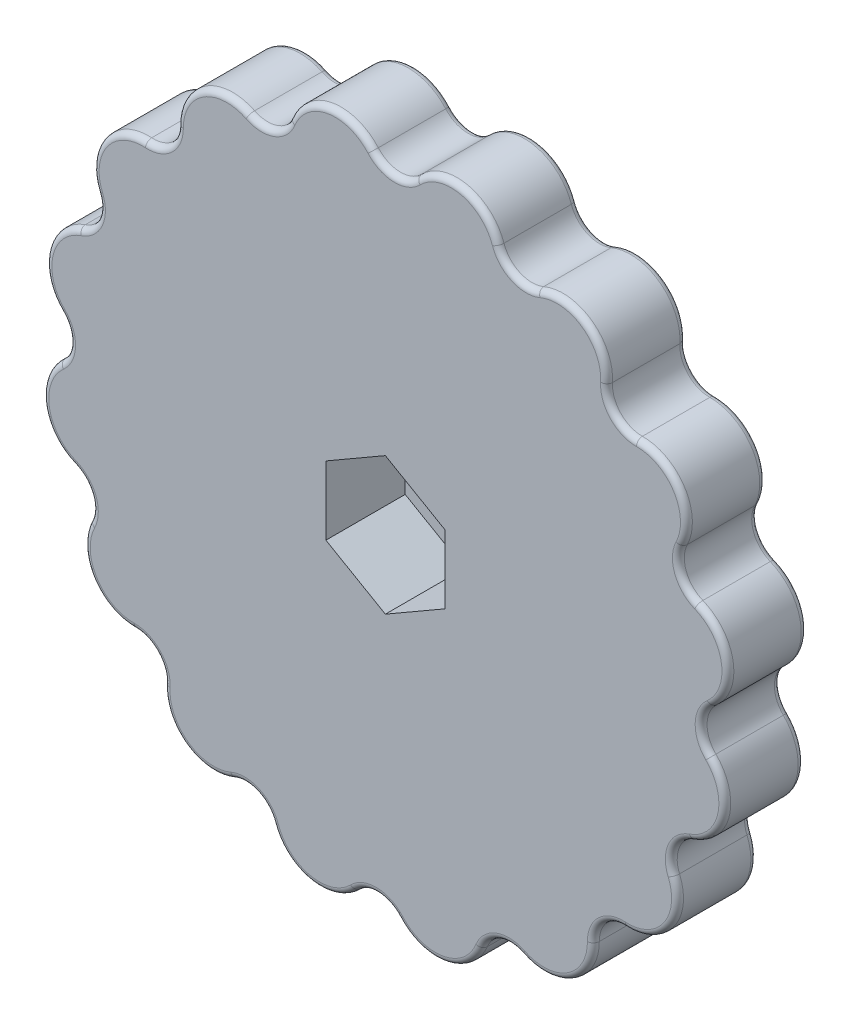
SolidWorks part; units mm, degrees
material "ABS"
ref_plane "Front Plane" through (0, 0, 0) normal (0, 0, 1) x (1, 0, 0)
ref_plane "Top Plane" through (0, 0, 0) normal (0, 1, 0) x (1, 0, 0)
ref_plane "Right Plane" through (0, 0, 0) normal (1, 0, 0) x (0, 0, -1)
ref_plane "Plane1" through (0, 0, 2) normal (0, 0, -1) x (-1, 0, 0)
sketch "Sketch1" plane through (0, 0, 2) normal (0, 0, -1) x (-1, 0, 0)
  line L193 (-20.6157, 1.931) -> (20.5827, 1.931) construction
  arc A1 (-1.5391, 16.3806) -> (0.6549, 16.4397) centre (-0.4696, 17.4324) ccw
  arc A32 (4.8467, 15.7227) -> (6.8963, 14.9377) centre (6.2372, 16.2852) ccw
  arc A33 (0.6549, 16.4397) -> (4.8467, 15.7227) centre (2.5291, 14.7853) cw
  arc A34 (6.8963, 14.9377) -> (10.4946, 12.6712) centre (7.9947, 12.6919) cw
  arc A38 (10.4946, 12.6712) -> (12.0877, 11.1616) centre (11.9945, 12.6587) ccw
  arc A39 (12.0877, 11.1616) -> (14.5448, 7.6905) centre (12.2431, 8.6664) cw
  arc A40 (14.5448, 7.6905) -> (15.439, 5.6862) centre (15.9258, 7.105) ccw
  arc A44 (15.439, 5.6862) -> (16.3806, 1.5391) centre (14.6276, 3.3215) cw
  arc A45 (16.3806, 1.5391) -> (16.4397, -0.6549) centre (17.4324, 0.4696) ccw
  arc A46 (16.4397, -0.6549) -> (15.7227, -4.8467) centre (14.7853, -2.5291) cw
  arc A50 (15.7227, -4.8467) -> (14.9377, -6.8963) centre (16.2852, -6.2372) ccw
  arc A51 (14.9377, -6.8963) -> (12.6712, -10.4946) centre (12.6919, -7.9947) cw
  arc A52 (12.6712, -10.4946) -> (11.1616, -12.0877) centre (12.6587, -11.9945) ccw
  arc A56 (11.1616, -12.0877) -> (7.6905, -14.5448) centre (8.6664, -12.2431) cw
  arc A57 (7.6905, -14.5448) -> (5.6862, -15.439) centre (7.105, -15.9258) ccw
  arc A58 (5.6862, -15.439) -> (1.5391, -16.3806) centre (3.3215, -14.6276) cw
  arc A62 (1.5391, -16.3806) -> (-0.6549, -16.4397) centre (0.4696, -17.4324) ccw
  arc A63 (-0.6549, -16.4397) -> (-4.8467, -15.7227) centre (-2.5291, -14.7853) cw
  arc A64 (-4.8467, -15.7227) -> (-6.8963, -14.9377) centre (-6.2372, -16.2852) ccw
  arc A68 (-6.8963, -14.9377) -> (-10.4946, -12.6712) centre (-7.9947, -12.6919) cw
  arc A69 (-10.4946, -12.6712) -> (-12.0877, -11.1616) centre (-11.9945, -12.6587) ccw
  arc A70 (-12.0877, -11.1616) -> (-14.5448, -7.6905) centre (-12.2431, -8.6664) cw
  arc A74 (-14.5448, -7.6905) -> (-15.439, -5.6862) centre (-15.9258, -7.105) ccw
  arc A75 (-15.439, -5.6862) -> (-16.3806, -1.5391) centre (-14.6276, -3.3215) cw
  arc A76 (-16.3806, -1.5391) -> (-16.4397, 0.6549) centre (-17.4324, -0.4696) ccw
  arc A77 (-16.4397, 0.6549) -> (-15.7227, 4.8467) centre (-14.7853, 2.5291) cw
  arc A80 (-15.7227, 4.8467) -> (-14.9377, 6.8963) centre (-16.2852, 6.2372) ccw
  arc A83 (-14.9377, 6.8963) -> (-12.6712, 10.4946) centre (-12.6919, 7.9947) cw
  arc A86 (-12.6712, 10.4946) -> (-11.1616, 12.0877) centre (-12.6587, 11.9945) ccw
  arc A89 (-11.1616, 12.0877) -> (-7.6905, 14.5448) centre (-8.6664, 12.2431) cw
  arc A92 (-7.6905, 14.5448) -> (-5.6862, 15.439) centre (-7.105, 15.9258) ccw
  arc A95 (-5.6862, 15.439) -> (-1.5391, 16.3806) centre (-3.3215, 14.6276) cw
  point P79 (0, 0)
  point P108 (0, 0)
  point P252 (0, 0)
  dimension "D1" = 2.5
  dimension "D2" = 3
  dimension "D3" = 16
  dimension "D5" = 30
extrude "Boss-Extrude1" add sketch "Sketch1" against normal blind 4
sketch "Sketch2" plane through (0, 0, 2) normal (0, 0, -1) x (-1, 0, 0)
  circle A0 centre (0, 0) radius 6
  dimension "D1" = 12
extrude "Boss-Extrude2" add sketch "Sketch2" along normal blind 2
sketch "Sketch3" plane through (0, 0, 6) normal (0, 0, -1) x (-1, 0, 0)
  circle A0 centre (0, 0) radius 1.8
  dimension "D1" = 3.6
extrude "Cut-Extrude1" cut sketch "Sketch3" along normal up to next
sketch "Sketch4" plane through (0, 0, 6) normal (0, 0, 1) x (1, 0, 0)
  line L7 (0, 3.4641) -> (-3, 1.7321)
  line L8 (-3, 1.7321) -> (-3, -1.7321)
  line L9 (-3, -1.7321) -> (0, -3.4641)
  line L10 (0, -3.4641) -> (3, -1.7321)
  line L11 (3, -1.7321) -> (3, 1.7321)
  line L12 (3, 1.7321) -> (0, 3.4641)
  circle A0 centre (0, 0) radius 3 construction
  dimension "D1" = 6
extrude "Cut-Extrude2" cut sketch "Sketch4" against normal blind 4
fillet "Fillet1" radius 0.5 1 edges at (6, 0, 2)
fillet "Fillet2" radius 0.3 64 edges at (0.4292, 15.933, 6) (0.4292, 15.933, 2) (-2.9506, 17.2495, 6) (-5.7007, 14.8844, 6) (-9.3271, 14.8073, 6) (-10.9628, 11.5698, 6) (-14.2836, 10.1108, 6) (-14.5559, 6.4939, 6) (-17.0656, 3.8751, 6) (-15.933, 0.4292, 6) (-17.2495, -2.9506, 6) (-14.8844, -5.7007, 6) (-14.8073, -9.3271, 6) (-11.5698, -10.9628, 6) (-10.1108, -14.2836, 6) (-6.4939, -14.5559, 6) (-3.8751, -17.0656, 6) (-0.4292, -15.933, 6) (2.9506, -17.2495, 6) (5.7007, -14.8844, 6) (9.3271, -14.8073, 6) (10.9628, -11.5698, 6) (14.2836, -10.1108, 6) (14.5559, -6.4939, 6) (17.0656, -3.8751, 6) (15.933, -0.4292, 6) (17.2495, 2.9506, 6) (14.8844, 5.7007, 6) (14.8073, 9.3271, 6) (11.5698, 10.9628, 6) (10.1108, 14.2836, 6) (6.4939, 14.5559, 6) (3.8751, 17.0656, 6) (-2.9506, 17.2495, 2) (-5.7007, 14.8844, 2) (-9.3271, 14.8073, 2) (-10.9628, 11.5698, 2) (-14.2836, 10.1108, 2) (-14.5559, 6.4939, 2) (-17.0656, 3.8751, 2) (-15.933, 0.4292, 2) (-17.2495, -2.9506, 2) (-14.8844, -5.7007, 2) (-14.8073, -9.3271, 2) (-11.5698, -10.9628, 2) (-10.1108, -14.2836, 2) (-6.4939, -14.5559, 2) (-3.8751, -17.0656, 2) (-0.4292, -15.933, 2) (2.9506, -17.2495, 2) (5.7007, -14.8844, 2) (9.3271, -14.8073, 2) (10.9628, -11.5698, 2) (14.2836, -10.1108, 2) (14.5559, -6.4939, 2) (17.0656, -3.8751, 2) (15.933, -0.4292, 2) (17.2495, 2.9506, 2) (14.8844, 5.7007, 2) (14.8073, 9.3271, 2) (11.5698, 10.9628, 2) (10.1108, 14.2836, 2) (6.4939, 14.5559, 2) (3.8751, 17.0656, 2)
